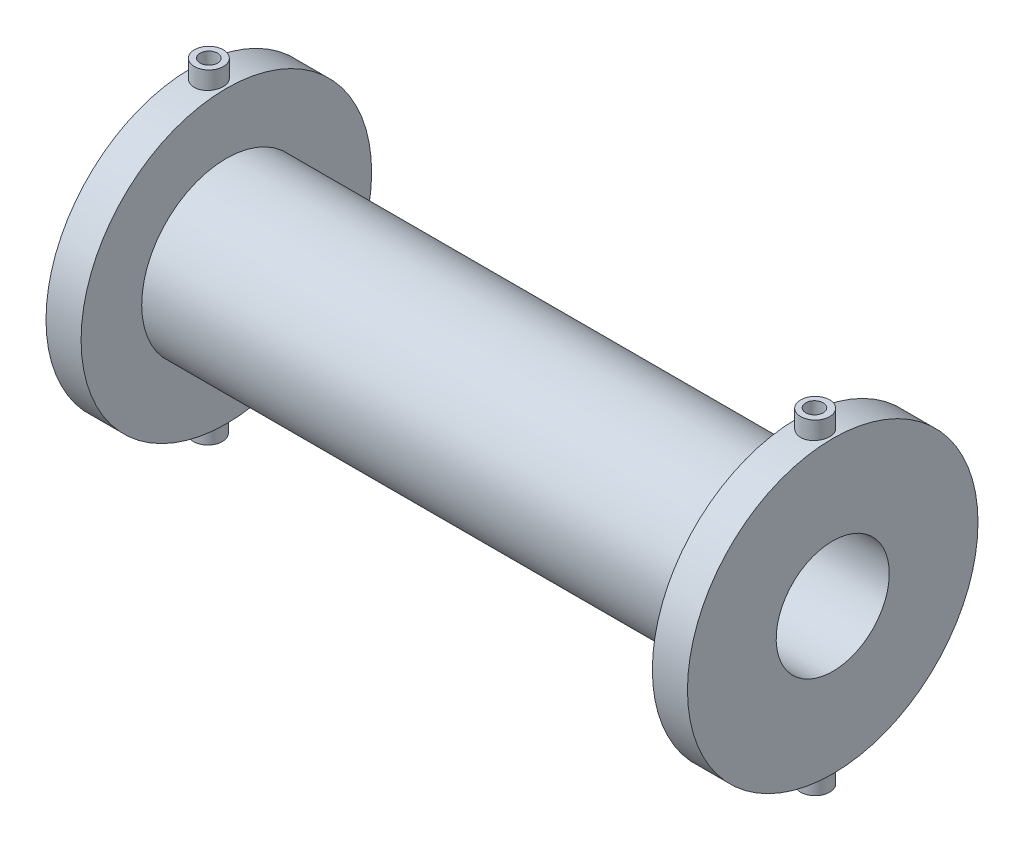
SolidWorks part; units mm, degrees
ref_plane "Alzado" through (0, 0, 0) normal (0, 0, 1) x (1, 0, 0)
ref_plane "Planta" through (0, 0, 0) normal (0, 1, 0) x (1, 0, 0)
ref_plane "Vista lateral" through (0, 0, 0) normal (1, 0, 0) x (0, 0, -1)
sketch "Ejes" plane through (0, 0, 0) normal (0, 0, 1) x (1, 0, 0)
  line L0 (-125, 0) -> (125, 0) construction
  line L1 (0, 0) -> (0, 19.5) construction
  point P5 (0, 0)
  dimension "D1" = 19.5
  dimension "D2" = 250
sketch "Camisa" plane through (0, 0, 0) normal (0, 0, 1) x (1, 0, 0)
  line L0 (-110.61, 19.5) -> (110.61, 19.5)
  line L1 (-110.61, 19.5) -> (-110.61, 50.1)
  line L2 (-110.61, 50.1) -> (-98.51, 50.1)
  line L3 (-98.51, 50.1) -> (-98.51, 29.1939)
  line L4 (-98.51, 29.1939) -> (98.51, 29.1939)
  line L5 (98.51, 29.1939) -> (98.51, 50.1)
  line L6 (98.51, 50.1) -> (110.61, 50.1)
  line L7 (110.61, 50.1) -> (110.61, 19.5)
  line L8 (100.51, 48.1) -> (108.61, 48.1)
  line L9 (108.61, 48.1) -> (108.61, 21.5)
  line L10 (100.51, 48.1) -> (100.51, 27.1939)
  line L11 (100.51, 27.1939) -> (-100.51, 27.1939)
  line L12 (108.61, 21.5) -> (-108.61, 21.5)
  line L13 (-108.61, 21.5) -> (-108.61, 48.1)
  line L14 (-108.61, 48.1) -> (-100.51, 48.1)
  line L15 (-100.51, 48.1) -> (-100.51, 27.1939)
  line L16 (0, 19.5) -> (0, 0) construction
  line L17 (125, 0) -> (-125, 0) construction
  line L18 (-104.8799, 49.8161) -> (-104.56, 50.1) construction
  line L19 (-104.8799, -50.3839) -> (-104.8799, 49.8161) construction
  line L20 (104.56, 50.1) -> (104.56, -50.1) construction
  point P2 (0, 19.5)
  point P5 (0, 19.5)
  point P16 (-98.51, 39.6469)
  point P27 (-104.56, 50.1)
  dimension "D1" = 221.22
  dimension "D2" = 30.6
  dimension "D3" = 12.1
  dimension "D4" = 12.1
  dimension "D5" = 9.6939
  dimension "D6" = 2
  dimension "D7" = 2
  dimension "D8" = 2
  dimension "D9" = 2
  dimension "D10" = 2
  dimension "D11" = 2
  dimension "D12" = 2
  dimension "D13" = 2
  dimension "D14" = 30.6
  dimension "D15" = 100.2
  dimension "D16" = 100.2
revolve "Revolución3" add sketch "Camisa" angle 360 about L17
sketch3d "Croquis3D2" plane through (0, 0, 0) normal (0, 0, 1) x (1, 0, 0)
ref_plane "Plano1" through (0, 50.1, 0) normal (0, 1, 0) x (1, 0, 0)
ref_plane "Plano2" through (0, 50.1, 0) normal (0, 1, 0) x (1, 0, 0)
ref_plane "Plano3" through (0, -50.1, 0) normal (0, -1, 0) x (-1, 0, 0)
ref_plane "Plano4" through (0, -50.1, 0) normal (0, -1, 0) x (-1, 0, 0)
sketch "Croquis3" plane through (0, 50.1, 0) normal (0, 1, 0) x (1, 0, 0)
  line L0 (-110.61, 0) -> (-98.51, 0) construction
  circle A0 centre (-104.56, 0) radius 5
  dimension "D1" = 10
extrude "Saliente-Extruir1" add sketch "Croquis3" along normal mid plane 12
sketch "Croquis4" plane through (0, 56.1, 0) normal (0, 1, 0) x (1, 0, 0)
  circle A0 centre (-104.56, 0) radius 3
  dimension "D1" = 6
extrude "Cortar-Extruir1" cut sketch "Croquis4" against normal blind 12
sketch "Croquis5" plane through (0, 50.1, 0) normal (0, 1, 0) x (1, 0, 0)
  line L0 (98.51, 0) -> (110.61, 0) construction
  circle A0 centre (104.56, 0) radius 5
  dimension "D1" = 10
extrude "Saliente-Extruir2" add sketch "Croquis5" along normal mid plane 12
sketch "Croquis6" plane through (0, 56.1, 0) normal (0, 1, 0) x (1, 0, 0)
  circle A0 centre (104.3116, 0) radius 3
  dimension "D1" = 6
extrude "Cortar-Extruir2" cut sketch "Croquis6" against normal blind 12
sketch "Croquis8" plane through (0, -50.1, 0) normal (0, -1, 0) x (-1, 0, 0)
  circle A0 centre (104.8799, 0) radius 5
  dimension "D1" = 10
extrude "Saliente-Extruir4" add sketch "Croquis8" along normal mid plane 12
sketch "Croquis9" plane through (0, -56.1, 0) normal (0, -1, 0) x (1, 0, 0)
  circle A0 centre (-104.8799, 0) radius 3
  dimension "D1" = 6
extrude "Cortar-Extruir4" cut sketch "Croquis9" against normal blind 12
sketch "Croquis10" plane through (0, -50.1, 0) normal (0, -1, 0) x (-1, 0, 0)
  circle A0 centre (-104.56, 0) radius 5
  dimension "D1" = 10
extrude "Saliente-Extruir5" add sketch "Croquis10" along normal mid plane 12
sketch "Croquis11" plane through (0, -56.1, 0) normal (0, -1, 0) x (1, 0, 0)
  line L0 (100.51, 0) -> (108.61, 0) construction
  circle A0 centre (104.56, 0) radius 3
  dimension "D1" = 6
extrude "Cortar-Extruir5" cut sketch "Croquis11" against normal blind 12
